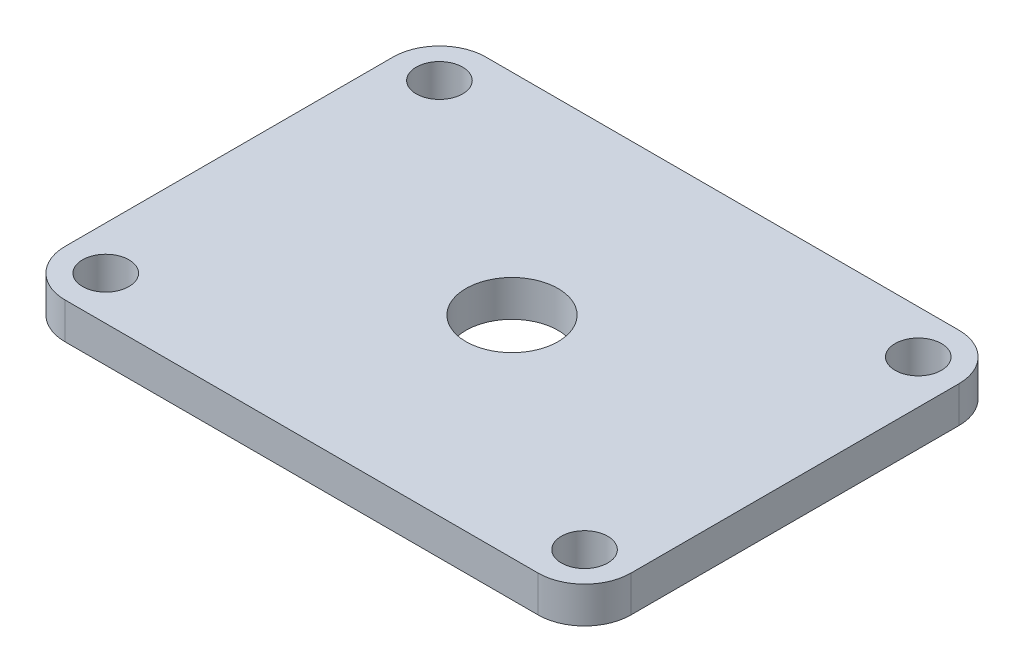
SolidWorks part; units mm, degrees
ref_plane "Front Plane" through (0, 0, 0) normal (0, 0, 1) x (1, 0, 0)
ref_plane "Top Plane" through (0, 0, 0) normal (0, 1, 0) x (1, 0, 0)
ref_plane "Right Plane" through (0, 0, 0) normal (1, 0, 0) x (0, 0, -1)
sketch "Sketch1" plane through (0, 0, 0) normal (0, 1, 0) x (1, 0, 0)
  line L0 (0, 29) -> (39, 0) construction
  line L1 (3.2, 0) -> (35.8, 0)
  line L2 (0, 3.2) -> (0, 25.8)
  line L3 (3.2, 29) -> (35.8, 29)
  line L4 (39, 3.2) -> (39, 25.8)
  line L5 (39, 29) -> (0, 0) construction
  line L7 (3, 26) -> (36, 26) construction
  line L8 (3, 26) -> (3, 3) construction
  line L9 (3, 3) -> (36, 3) construction
  line L10 (36, 26) -> (36, 3) construction
  line L11 (3, 26) -> (36, 3) construction
  line L12 (3, 3) -> (36, 26) construction
  circle A0 centre (19.5, 14.5) radius 3.175
  circle A1 centre (3, 26) radius 1.6
  circle A2 centre (36, 26) radius 1.6
  circle A3 centre (36, 3) radius 1.6
  circle A4 centre (3, 3) radius 1.6
  arc A5 (3.2, 0) -> (0, 3.2) centre (3.2, 3.2) cw
  arc A6 (35.8, 0) -> (39, 3.2) centre (35.8, 3.2) ccw
  arc A7 (35.8, 29) -> (39, 25.8) centre (35.8, 25.8) cw
  arc A8 (0, 25.8) -> (3.2, 29) centre (3.2, 25.8) cw
  dimension "D3" = 6.35
  dimension "D6" = 3.2
  dimension "D7" = 3.2
  dimension "D1" = 39
  dimension "D2" = 29
  dimension "D4" = 33
  dimension "D5" = 23
extrude "Boss-Extrude1" add sketch "Sketch1" along normal blind 2.5
